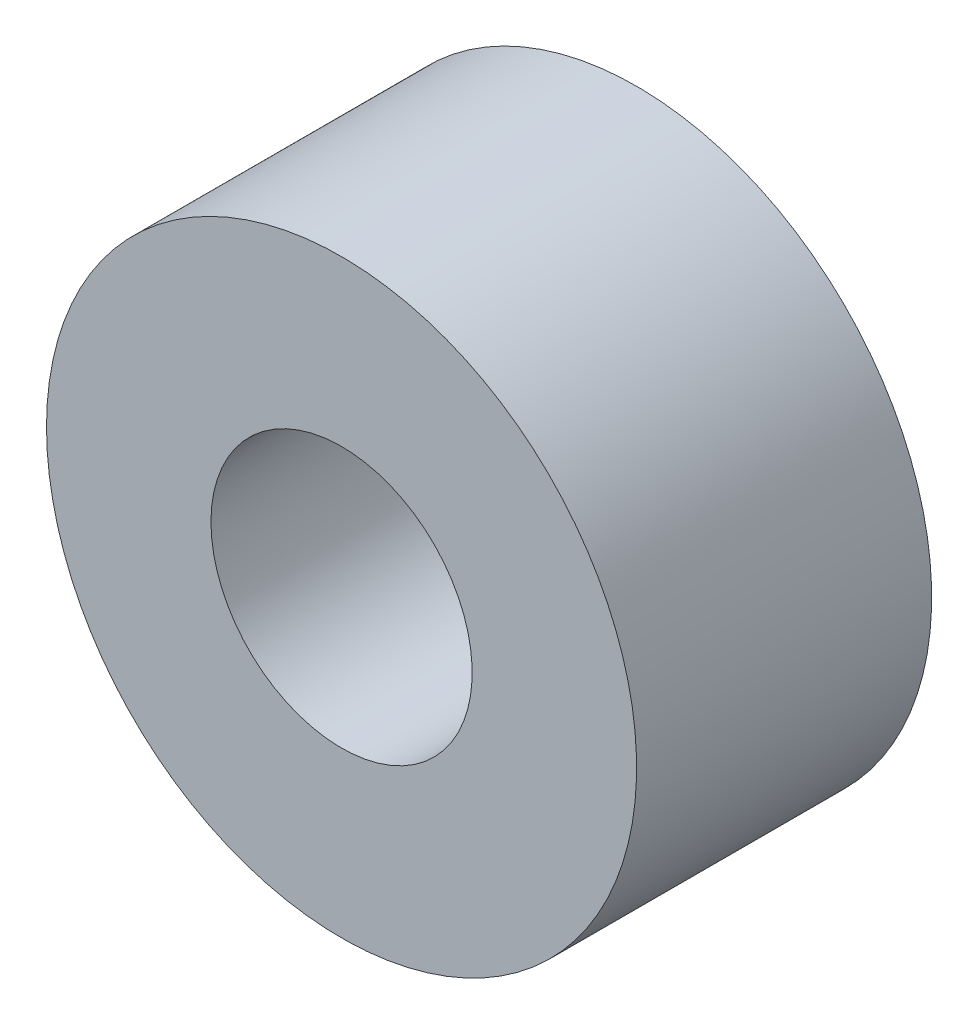
SolidWorks part; units mm, degrees
material "Plain Carbon Steel"
ref_plane "Front Plane" through (0, 0, 0) normal (0, 0, 1) x (1, 0, 0)
ref_plane "Top Plane" through (0, 0, 0) normal (0, 1, 0) x (1, 0, 0)
ref_plane "Right Plane" through (0, 0, 0) normal (1, 0, 0) x (0, 0, -1)
sketch "Sketch1" plane through (0, 0, 0) normal (0, 0, 1) x (1, 0, 0)
  circle A0 centre (0, 0) radius 4.7625
  circle A1 centre (0, 0) radius 2.1082
  dimension "OD" = 9.525
  dimension "ID" = 4.2164
extrude "Extrude1" add sketch "Sketch1" along normal mid plane 4.7625
sketch "Sketch2" plane through (0, 0, 0) normal (1, 0, 0) x (0, 0, -1)
  line L0 (-2.3813, -2.1082) -> (2.3812, -2.1082) construction
  line L3 (2.3812, 2.1082) -> (-2.3813, 2.1082) construction
  line L5 (-2.3813, -2.1082) -> (2.3812, -2.1082)
  line L6 (2.3812, 2.1082) -> (-2.3813, 2.1082)
sketch "Sketch4" plane through (0, 0, 2.3813) normal (0, 0, 1) x (1, 0, 0)
  line L0 (0, 0) -> (-1.4907, 1.4907)
  line L1 (0, -5.2388) -> (0, 5.2388) construction
  circle A0 centre (0, 0) radius 2.1082 construction
  dimension "D1" = 45
